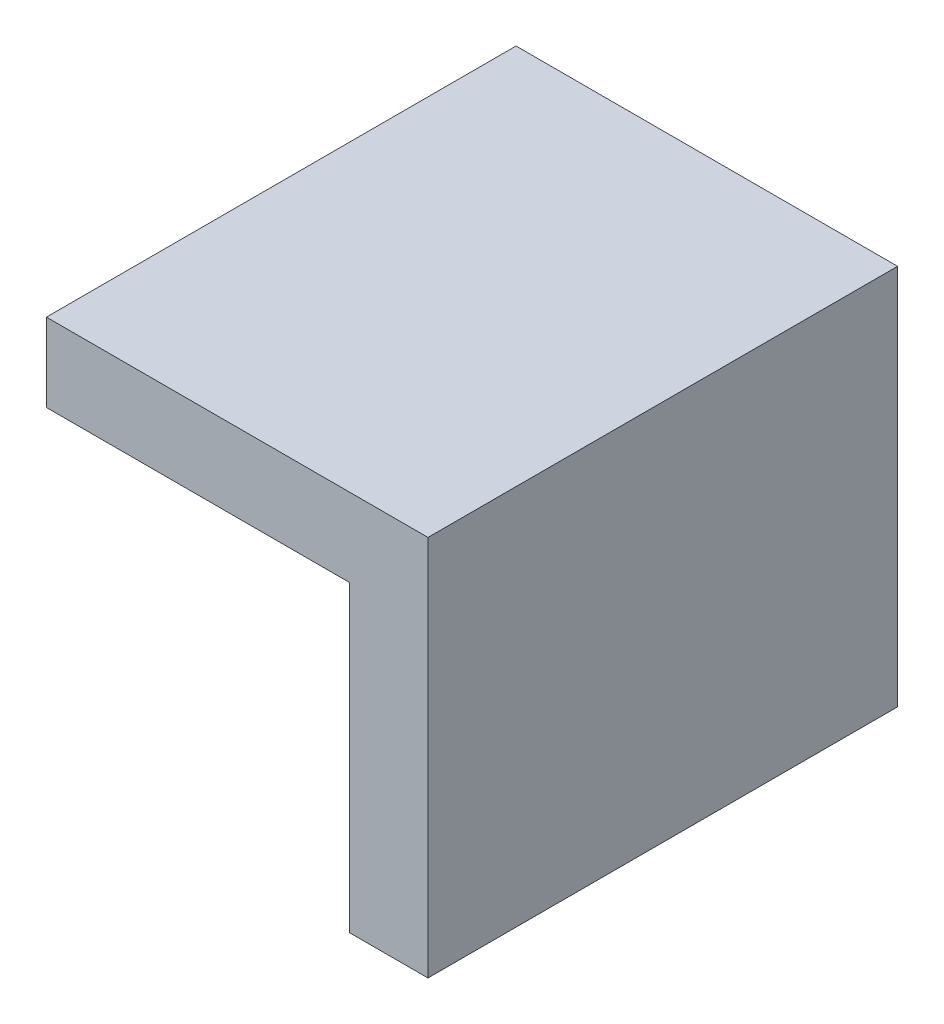
SolidWorks part; units mm, degrees
ref_plane "Спереди" through (0, 0, 0) normal (0, 0, 1) x (1, 0, 0)
ref_plane "Сверху" through (0, 0, 0) normal (0, 1, 0) x (1, 0, 0)
ref_plane "Справа" through (0, 0, 0) normal (1, 0, 0) x (0, 0, -1)
sketch "Эскиз1" plane through (0, 0, 0) normal (0, 0, 1) x (1, 0, 0)
  line L1 (-3.9, -3.9) -> (3.9, -3.9)
  line L2 (-3.9, -3.9) -> (-3.9, 3.9)
  line L3 (-3.9, 3.9) -> (3.9, 3.9)
  line L4 (3.9, -3.9) -> (3.9, 3.9)
  line L5 (-3.9, -3.9) -> (3.9, 3.9) construction
  line L6 (-3.9, 3.9) -> (3.9, -3.9) construction
  point P0 (0, 0)
  dimension "D1" = 7.8
  dimension "D2" = 7.8
extrude "Бобышка-Вытянуть1" add sketch "Эскиз1" along normal blind 9.6
sketch "Эскиз6" plane through (0, 0, 9.6) normal (0, 0, 1) x (1, 0, 0)
  line L0 (3.9, 3.9) -> (-3.9, 3.9) construction
  line L1 (-3.9, -3.9) -> (2.3, -3.9)
  line L2 (-3.9, -3.9) -> (-3.9, 2.3)
  line L3 (-3.9, 2.3) -> (2.3, 2.3)
  line L4 (2.3, -3.9) -> (2.3, 2.3)
  line L5 (3.9, -3.9) -> (3.9, 3.9) construction
  dimension "D1" = 1.6
  dimension "D2" = 1.6
extrude "Вырез-Вытянуть8" cut sketch "Эскиз6" against normal blind 7.6
sketch "Эскиз9" plane through (0, 0, 0) normal (0, 0, -1) x (-1, 0, 0)
  circle A0 centre (0, 0) radius 2.5
extrude "Вырез-Вытянуть9" cut sketch "Эскиз9" against normal blind 1.8
